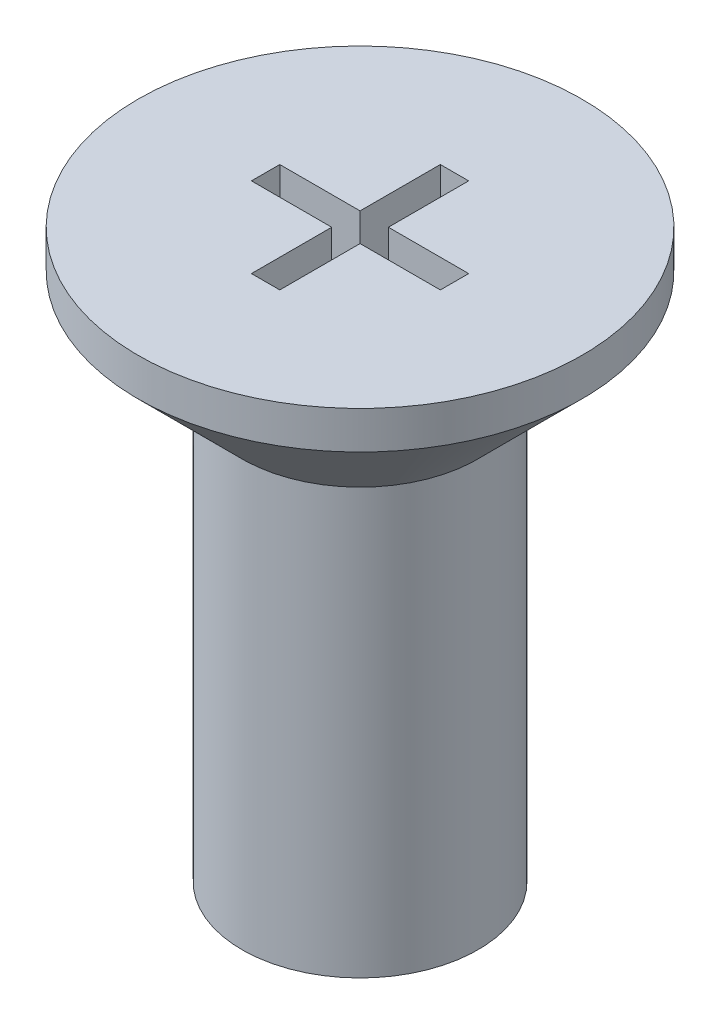
SolidWorks part; units mm, degrees
material "Plain Carbon Steel"
ref_plane "Front Plane" through (0, 0, 0) normal (0, 0, 1) x (1, 0, 0)
ref_plane "Top Plane" through (0, 0, 0) normal (0, 1, 0) x (1, 0, 0)
ref_plane "Right Plane" through (0, 0, 0) normal (1, 0, 0) x (0, 0, -1)
sketch "Sketch1" plane through (0, 0, 0) normal (0, 0, 1) x (1, 0, 0)
  line L0 (0, 0) -> (1.25, 0)
  line L1 (1.25, 0) -> (1.25, 4.5)
  line L2 (1.25, 4.5) -> (2.35, 5.6)
  line L3 (2.35, 5.6) -> (2.35, 6)
  line L4 (2.35, 6) -> (0, 6)
  line L5 (0, 6) -> (0, 0)
  dimension "D1" = 1.25
  dimension "D2" = 6
  dimension "D3" = 45
  dimension "D4" = 2.35
  dimension "D5" = 1.5
revolve "Revolve1" add sketch "Sketch1" angle 360 about L5
sketch "Sketch2" plane through (0, 6, 0) normal (0, 1, 0) x (1, 0, 0)
  line L0 (0, 1) -> (0.15, 1)
  line L1 (0.15, 1) -> (0.15, 0.15)
  line L2 (0.15, 0.15) -> (1, 0.15)
  line L3 (1, 0.15) -> (1, -0.15)
  line L4 (1, -0.15) -> (0.15, -0.15)
  line L5 (0.15, -0.15) -> (0.15, -1)
  line L6 (0.15, -1) -> (-0.15, -1)
  line L7 (-0.15, -1) -> (-0.15, -0.15)
  line L8 (-0.15, -0.15) -> (-1, -0.15)
  line L9 (-1, -0.15) -> (-1, 0.15)
  line L10 (-1, 0.15) -> (-0.15, 0.15)
  line L11 (-0.15, 0.15) -> (-0.15, 1)
  line L12 (-0.15, 1) -> (0, 1)
  dimension "D1" = 2
  dimension "D2" = 2
  dimension "D3" = 1
  dimension "D4" = 1
  dimension "D5" = 0.15
  dimension "D6" = 0.3
  dimension "D7" = 0.3
  dimension "D8" = 0.15
extrude "Cut-Extrude1" cut sketch "Sketch2" against normal blind 1
